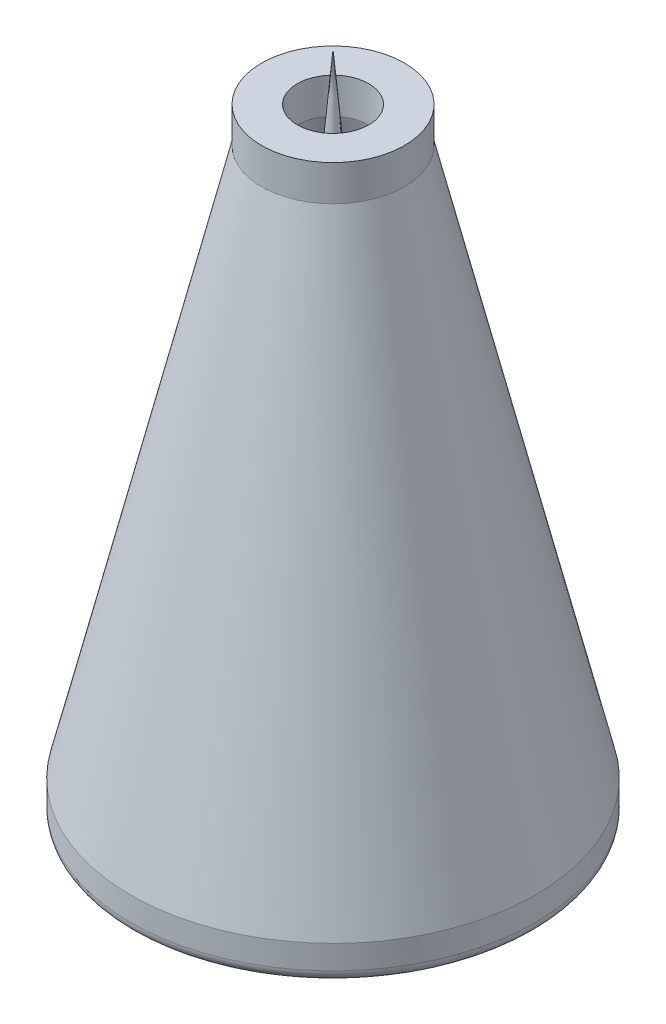
SolidWorks part; units mm, degrees
ref_plane "Front Plane" through (0, 0, 0) normal (0, 0, 1) x (1, 0, 0)
ref_plane "Top Plane" through (0, 0, 0) normal (0, 1, 0) x (1, 0, 0)
ref_plane "Right Plane" through (0, 0, 0) normal (1, 0, 0) x (0, 0, -1)
sketch "Sketch1" plane through (0, 0, 0) normal (0, 0, 1) x (1, 0, 0)
  line L0 (-70, 0) -> (-85, 0)
  line L1 (-85, 0) -> (-85, 15)
  line L2 (-70, 0) -> (-70, 15)
  line L3 (0, 0) -> (0, 260) construction
  line L4 (-15, 260) -> (-30, 260)
  line L5 (-30, 260) -> (-30, 245)
  line L6 (-30, 245) -> (-85, 15)
  line L7 (-15, 260) -> (-15, 245)
  line L8 (-15, 245) -> (-70, 15)
  dimension "D1" = 15
  dimension "D2" = 70
  dimension "D3" = 15
  dimension "D4" = 260
  dimension "D5" = 15
  dimension "D6" = 15
  dimension "D7" = 15
  dimension "D8" = 245
revolve "Revolve1" add sketch "Sketch1" angle 360 about L3
fillet "Fillet1" radius 5 2 edges at (0, 0, -70) (0, 0, -85)
sketch "Sketch3" plane through (0, 0, 0) normal (0, 0, 1) x (1, 0, 0)
  line L0 (0, 50) -> (0, 350.9579) construction
  line L3 (0, 30) -> (0, 280)
  line L5 (0, 280) -> (-20, 50)
  arc A0 (-20, 50) -> (0, 30) centre (0, 50) ccw
  dimension "D1" = 40
  dimension "D2" = 250
  dimension "D3" = 50
  dimension "D4" = 230.8679
revolve "Revolve2" add sketch "Sketch3" angle 360 about L0
sketch "Sketch5" plane through (0, 0, 0) normal (1, 0, 0) x (0, 0, -1)
  line L0 (0, 0) -> (0, 206.2482) construction
  line L1 (-1, 62) -> (1, 62)
  line L2 (-1, 142) -> (1, 142)
  line L3 (-6, 137) -> (-6, 67)
  line L4 (6, 137) -> (6, 67)
  arc A0 (1, 62) -> (6, 67) centre (1, 67) ccw
  arc A1 (-1, 62) -> (-6, 67) centre (-1, 67) cw
  arc A2 (-1, 142) -> (-6, 137) centre (-1, 137) ccw
  arc A3 (1, 142) -> (6, 137) centre (1, 137) cw
  point P5 (0, 62)
  point P8 (0, 142)
  point P10 (6, 62)
  point P14 (-6, 62)
  point P19 (6, 142)
  dimension "D4" = 5
  dimension "D1" = 62
  dimension "D2" = 80
  dimension "D3" = 12
extrude "Boss-Extrude1" add sketch "Sketch5" along normal up to surface (58.7524 mm away)
pattern_circular "CirPattern1" count 3 over 360 about axis through (0, 0, 0) along (0, 1, 0) of "Boss-Extrude1"
